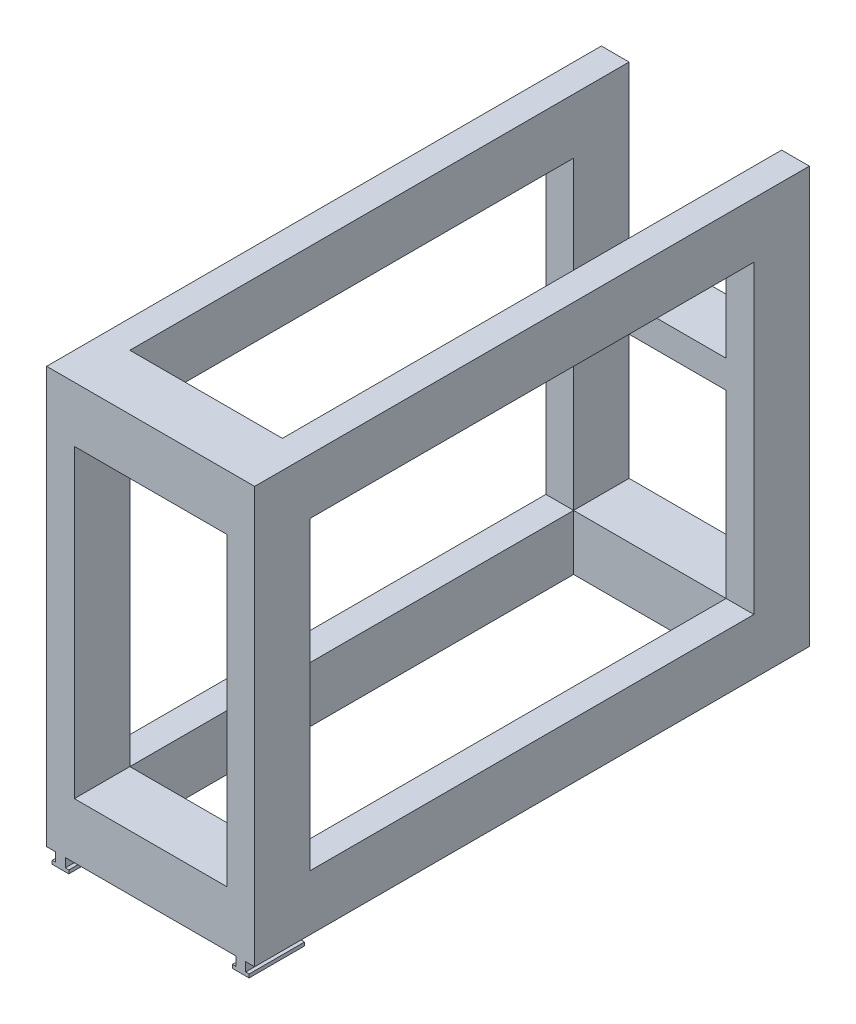
SolidWorks part; units mm, degrees
ref_plane "Front Plane" through (0, 0, 0) normal (0, 0, 1) x (1, 0, 0)
ref_plane "Top Plane" through (0, 0, 0) normal (0, 1, 0) x (1, 0, 0)
ref_plane "Right Plane" through (0, 0, 0) normal (1, 0, 0) x (0, 0, -1)
sketch "Sketch3" plane through (0, 0, 0) normal (0, 1, 0) x (1, 0, 0)
  line L1 (-95.25, -254) -> (95.25, -254)
  line L2 (-95.25, -254) -> (-95.25, 254)
  line L3 (-95.25, 254) -> (95.25, 254)
  line L4 (95.25, -254) -> (95.25, 254)
  line L5 (-95.25, -254) -> (95.25, 254) construction
  line L6 (-95.25, 254) -> (95.25, -254) construction
  point P0 (0, 0)
  dimension "D1" = 190.5
  dimension "D2" = 508
extrude "Boss-Extrude1" add sketch "Sketch3" along normal blind 381
sketch "Sketch4" plane through (95.25, 0, 0) normal (1, 0, 0) x (0, 0, -1)
  line L0 (254, 381) -> (254, 0) construction
  line L1 (-203.2, 50.8) -> (203.2, 50.8)
  line L2 (-203.2, 50.8) -> (-203.2, 330.2)
  line L3 (-203.2, 330.2) -> (203.2, 330.2)
  line L4 (203.2, 50.8) -> (203.2, 330.2)
  line L5 (-203.2, 50.8) -> (203.2, 330.2) construction
  line L6 (-203.2, 330.2) -> (203.2, 50.8) construction
  line L7 (-254, 381) -> (-254, 0) construction
  line L8 (-254, 381) -> (254, 381) construction
  point P0 (0, 190.5)
  point P8 (254, 190.5)
  dimension "D1" = 50.8
  dimension "D2" = 50.8
  dimension "D3" = 50.8
extrude "Cut-Extrude1" cut sketch "Sketch4" against normal blind 381
sketch "Sketch5" plane through (0, 0, -254) normal (0, 0, -1) x (-1, 0, 0)
  line L0 (-95.25, 381) -> (95.25, 381) construction
  line L1 (-69.85, 50.8) -> (69.85, 50.8)
  line L2 (-69.85, 50.8) -> (-69.85, 330.2)
  line L3 (-69.85, 330.2) -> (69.85, 330.2)
  line L4 (69.85, 50.8) -> (69.85, 330.2)
  line L5 (-69.85, 50.8) -> (69.85, 330.2) construction
  line L6 (-69.85, 330.2) -> (69.85, 50.8) construction
  line L7 (-95.25, 0) -> (95.25, 0) construction
  line L8 (95.25, 381) -> (95.25, 0) construction
  line L9 (-95.25, 381) -> (-95.25, 0) construction
  point P0 (0, 190.5)
  dimension "D1" = 50.8
  dimension "D2" = 50.8
  dimension "D3" = 25.4
  dimension "D4" = 25.4
extrude "Cut-Extrude2" cut sketch "Sketch5" against normal blind 924.052
sketch "Sketch6" plane through (0, 381, 0) normal (0, 1, 0) x (1, 0, 0)
  line L0 (-95.25, -254) -> (95.25, -254) construction
  line L1 (69.85, 203.2) -> (-69.85, 203.2)
  line L2 (69.85, 203.2) -> (69.85, -203.2)
  line L3 (69.85, -203.2) -> (-69.85, -203.2)
  line L4 (-69.85, 203.2) -> (-69.85, -203.2)
  line L5 (69.85, 203.2) -> (-69.85, -203.2) construction
  line L6 (69.85, -203.2) -> (-69.85, 203.2) construction
  line L8 (-95.25, 254) -> (-95.25, -254) construction
  point P0 (0, 0)
  dimension "D1" = 50.8
  dimension "D2" = 25.4
extrude "Cut-Extrude3" cut sketch "Sketch6" against normal blind 924.052
sketch "Sketch7" plane through (0, 0, 0) normal (0, -1, 0) x (1, 0, 0)
  line L0 (-95.25, 254) -> (95.25, 254) construction
  line L2 (-86.995, 203.2) -> (-78.105, 203.2)
  line L3 (-86.995, 203.2) -> (-86.995, 254)
  line L4 (-86.995, 254) -> (-78.105, 254)
  line L5 (-78.105, 203.2) -> (-78.105, 254)
  line L6 (-86.995, 203.2) -> (-78.105, 254) construction
  line L7 (-86.995, 254) -> (-78.105, 203.2) construction
  line L8 (69.85, 203.2) -> (-69.85, 203.2) construction
  line L9 (-69.85, 203.2) -> (-78.105, 203.2) construction
  line L10 (-86.995, 203.2) -> (-95.25, 203.2) construction
  line L11 (-95.25, -254) -> (-95.25, 254) construction
  point P0 (-82.55, 228.6)
  dimension "D1" = 8.89
extrude "Boss-Extrude2" add sketch "Sketch7" along normal blind 11.43
sketch "Sketch8" plane through (-78.105, 0, 0) normal (1, 0, 0) x (0, 0, -1)
  line L1 (-203.2, -11.43) -> (-254, -11.43)
  line L2 (-203.2, -11.43) -> (-203.2, -8.255)
  line L3 (-203.2, -8.255) -> (-254, -8.255)
  line L4 (-254, -11.43) -> (-254, -8.255)
  line L5 (-254, -11.43) -> (-254, 0) construction
  dimension "D1" = 3.175
extrude "Boss-Extrude3" add sketch "Sketch8" along normal blind 3.175
sketch "Sketch9" plane through (-86.995, 0, 0) normal (-1, 0, 0) x (0, 0, 1)
  line L0 (254, -11.43) -> (203.2, -11.43) construction
  line L1 (254, -11.43) -> (203.2, -11.43)
  line L2 (254, -11.43) -> (254, -8.255)
  line L3 (254, -8.255) -> (203.2, -8.255)
  line L4 (203.2, -11.43) -> (203.2, -8.255)
  line L5 (203.2, -11.43) -> (203.2, 0) construction
  line L7 (254, -11.43) -> (254, 0) construction
  dimension "D1" = 3.175
extrude "Boss-Extrude4" add sketch "Sketch9" along normal blind 3.175
mirror "Mirror1" about plane through (0, 0, 0) normal (1, 0, 0) of "Boss-Extrude3", "Boss-Extrude4", "Boss-Extrude2"
sketch "Sketch11" plane through (-69.85, 0, 0) normal (1, 0, 0) x (0, 0, -1)
  line L0 (203.2, 50.8) -> (203.2, 330.2) construction
  line L1 (203.2, 241.3) -> (254, 241.3)
  line L2 (203.2, 241.3) -> (203.2, 215.9)
  line L3 (203.2, 215.9) -> (254, 215.9)
  line L4 (254, 241.3) -> (254, 215.9)
  line L5 (254, 50.8) -> (254, 330.2) construction
  line L6 (-254, 0) -> (254, 0) construction
  dimension "D1" = 241.3
  dimension "D2" = 25.4
extrude "Boss-Extrude6" add sketch "Sketch11" along normal up to next contours L1 L4 L3 L2
sketch "Sketch12" plane through (0, 381, 0) normal (0, 1, 0) x (1, 0, 0)
  line L0 (95.25, 254) -> (-95.25, 254) construction
  line L1 (69.85, 203.2) -> (-69.85, 203.2)
  line L2 (69.85, 203.2) -> (69.85, 254)
  line L3 (69.85, 254) -> (-69.85, 254)
  line L4 (-69.85, 203.2) -> (-69.85, 254)
  line L5 (-69.85, 203.2) -> (-69.85, -203.2) construction
extrude "Cut-Extrude4" cut sketch "Sketch12" against normal up to next
